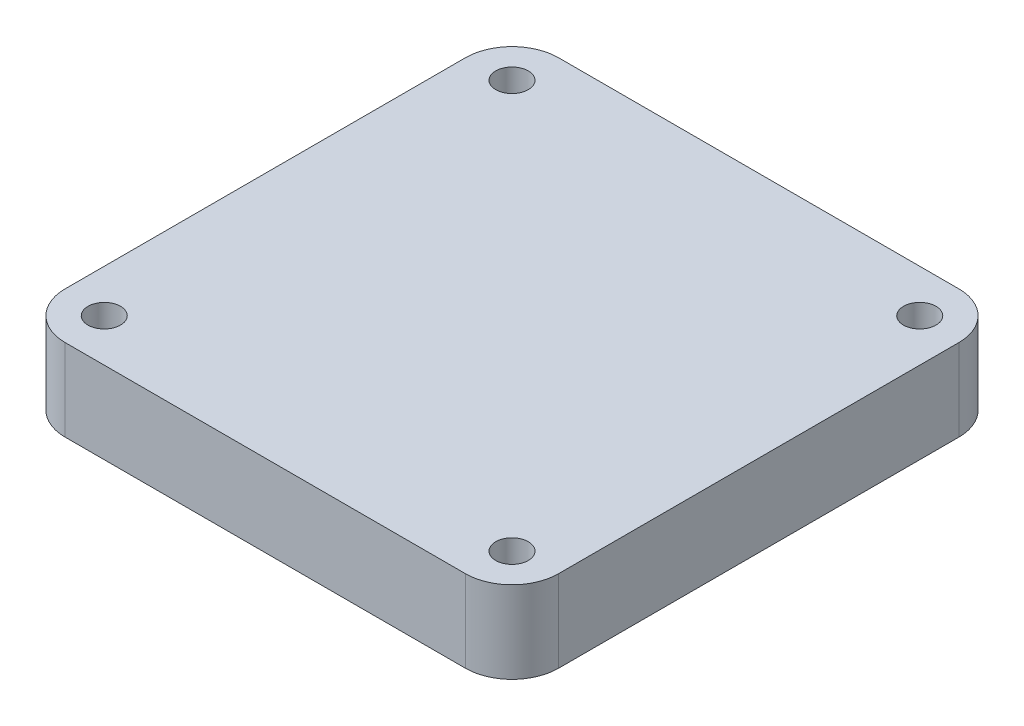
SolidWorks part; units mm, degrees
ref_plane "Front Plane" through (0, 0, 0) normal (0, 0, 1) x (1, 0, 0)
ref_plane "Top Plane" through (0, 0, 0) normal (0, 1, 0) x (1, 0, 0)
ref_plane "Right Plane" through (0, 0, 0) normal (1, 0, 0) x (0, 0, -1)
sketch "Sketch1" plane through (0, 0, 0) normal (0, 1, 0) x (1, 0, 0)
  line L1 (-26.5, 26.5) -> (26.5, 26.5)
  line L2 (-26.5, 26.5) -> (-26.5, -26.5)
  line L3 (-26.5, -26.5) -> (26.5, -26.5)
  line L4 (26.5, 26.5) -> (26.5, -26.5)
  line L5 (-26.5, 26.5) -> (26.5, -26.5) construction
  line L6 (-26.5, -26.5) -> (26.5, 26.5) construction
  line L7 (21.9, -21.9) -> (-21.9, -21.9) construction
  line L8 (21.9, -21.9) -> (21.9, 21.9) construction
  line L9 (21.9, 21.9) -> (-21.9, 21.9) construction
  line L10 (-21.9, -21.9) -> (-21.9, 21.9) construction
  line L11 (21.9, -21.9) -> (-21.9, 21.9) construction
  line L12 (21.9, 21.9) -> (-21.9, -21.9) construction
  circle A0 centre (-21.9, 21.9) radius 1.75
  circle A1 centre (21.9, 21.9) radius 1.75
  circle A2 centre (21.9, -21.9) radius 1.75
  circle A3 centre (-21.9, -21.9) radius 1.75
  point P0 (0, 0)
  point P6 (0, 0)
  dimension "D2" = 3.5
  dimension "D1" = 53
  dimension "D3" = 43.8
extrude "Boss-Extrude1" add sketch "Sketch1" along normal blind 8.8
fillet "Fillet1" radius 5 4 edges at (-26.5, 4.4, 26.5) (-26.5, 4.4, -26.5) (26.5, 4.4, -26.5) (26.5, 4.4, 26.5)
